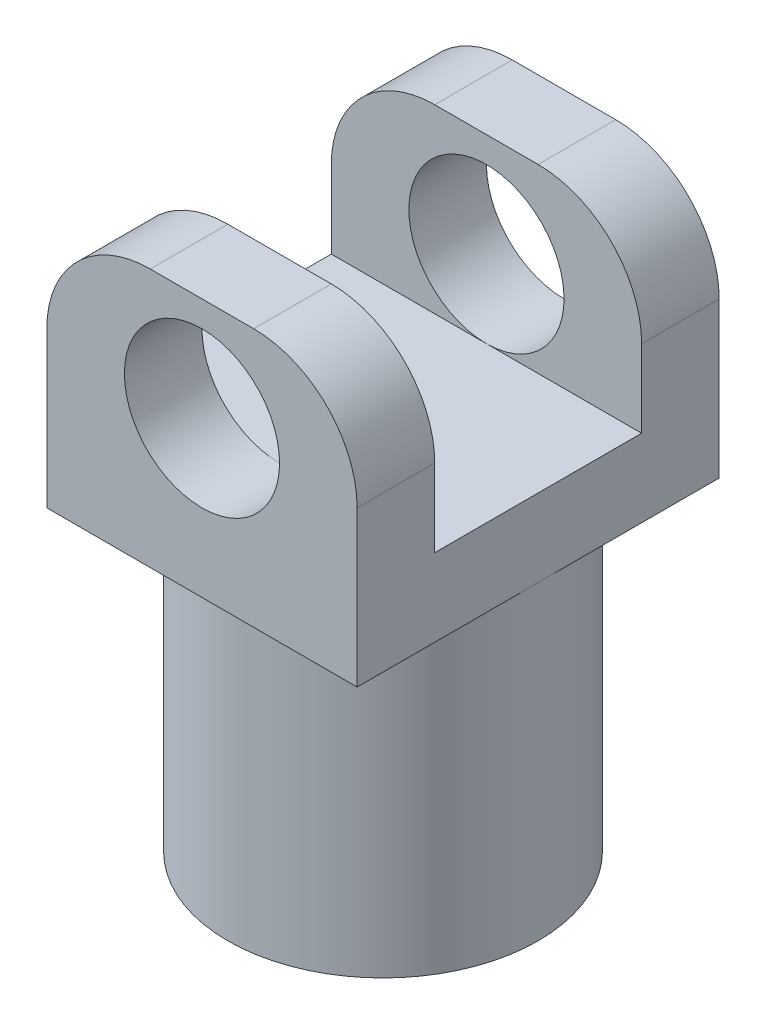
SolidWorks part; units mm, degrees
ref_plane "Front Plane" through (0, 0, 0) normal (0, 0, 1) x (1, 0, 0)
ref_plane "Top Plane" through (0, 0, 0) normal (0, 1, 0) x (1, 0, 0)
ref_plane "Right Plane" through (0, 0, 0) normal (1, 0, 0) x (0, 0, -1)
sketch "Sketch1" plane through (0, 0, 0) normal (0, 0, 1) x (1, 0, 0)
  line L1 (-5, 12.5) -> (5, 12.5)
  line L2 (-15, 2.5) -> (-15, -12.5)
  line L3 (-15, -12.5) -> (15, -12.5)
  line L4 (15, 2.5) -> (15, -12.5)
  line L5 (-15, 12.5) -> (15, -12.5) construction
  line L6 (-15, -12.5) -> (15, 12.5) construction
  arc A0 (-5, 12.5) -> (-15, 2.5) centre (-5, 2.5) ccw
  arc A1 (5, 12.5) -> (15, 2.5) centre (5, 2.5) cw
  circle A2 centre (0, 2.5) radius 7.5
  point P0 (0, 0)
  dimension "D3" = 10
  dimension "D4" = 15
  dimension "D5" = 10
  dimension "D6" = 15
  dimension "D1" = 30
  dimension "D2" = 25
extrude "Boss-Extrude1" add sketch "Sketch1" along normal blind 35
sketch "Sketch2" plane through (15, 0, 0) normal (1, 0, 0) x (0, 0, -1)
  line L0 (-27.5, 12.5) -> (-27.5, -5)
  line L1 (-35, 12.5) -> (0, 12.5) construction
  line L2 (-27.5, -5) -> (-7.5, -5)
  line L3 (-7.5, -5) -> (-7.5, 12.5)
  line L4 (-7.5, 12.5) -> (-27.5, 12.5)
  line L6 (-35, 12.5) -> (-35, 2.5) construction
  line L8 (-35, -12.5) -> (0, -12.5) construction
  dimension "D1" = 20
  dimension "D2" = 7.5
  dimension "D3" = 7.5
extrude "Cut-Extrude1" cut sketch "Sketch2" against normal blind 50
sketch "Sketch4" plane through (0, -12.5, 0) normal (0, -1, 0) x (1, 0, 0)
  line L0 (0, 0) -> (0, 35) construction
  line L1 (-15, 35) -> (15, 35) construction
  circle A0 centre (0, 17.5) radius 15
  dimension "D1" = 30
extrude "Boss-Extrude2" add sketch "Sketch4" along normal blind 30
sketch "Sketch6" plane through (0, -42.5, 0) normal (0, -1, 0) x (1, 0, 0)
  line L0 (0, 0) -> (0, 35) construction
  line L1 (-15, 35) -> (15, 35) construction
  circle A0 centre (0, 17.5) radius 9.525
  dimension "D1" = 19.05
extrude "Cut-Extrude2" cut sketch "Sketch6" against normal blind 30
